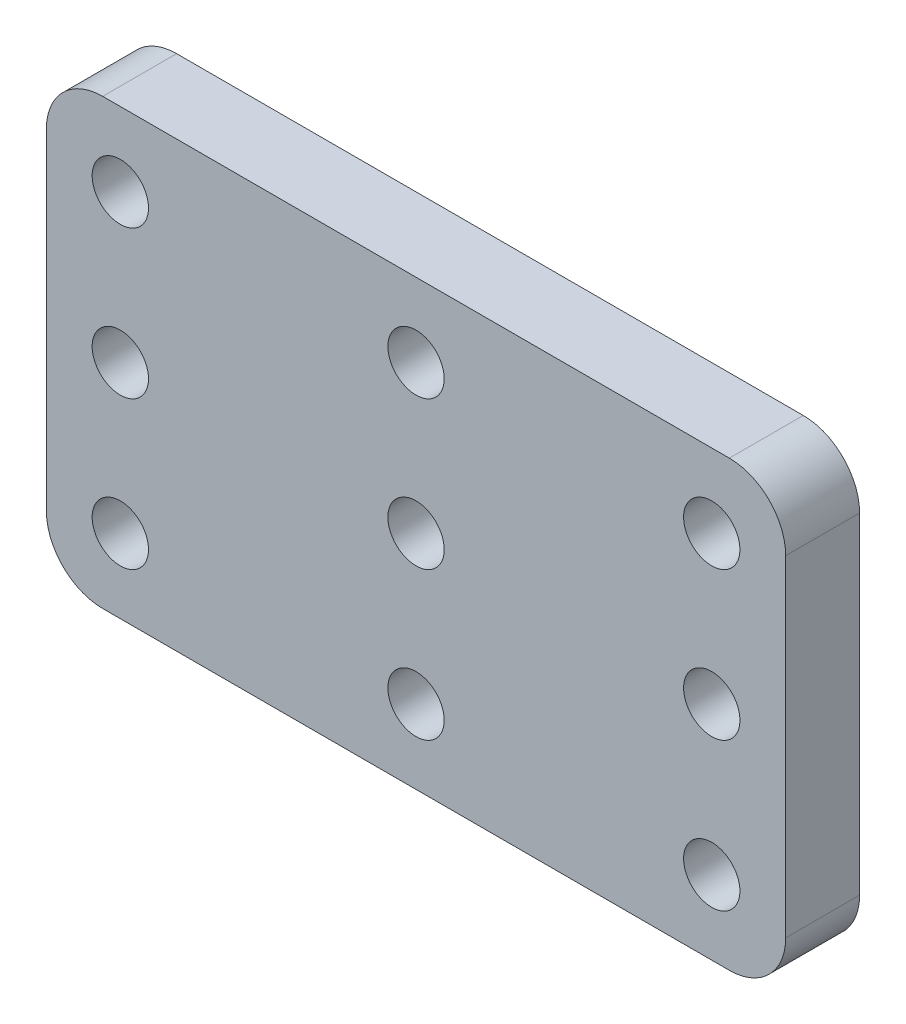
SolidWorks part; units mm, degrees
ref_plane "Front Plane" through (0, 0, 0) normal (0, 0, 1) x (1, 0, 0)
ref_plane "Top Plane" through (0, 0, 0) normal (0, 1, 0) x (1, 0, 0)
ref_plane "Right Plane" through (0, 0, 0) normal (1, 0, 0) x (0, 0, -1)
sketch "Sketch1" plane through (0, 0, 0) normal (0, 0, 1) x (1, 0, 0)
  line L1 (-24.9999, 15) -> (24.9999, 15)
  line L2 (-24.9999, 15) -> (-24.9999, -15)
  line L3 (-24.9999, -15) -> (25, -15)
  line L4 (24.9999, 15) -> (25, -15)
  line L5 (-24.9999, 15) -> (25, -15) construction
  line L6 (-24.9999, -15) -> (24.9999, 15) construction
  point P0 (0, 0)
  dimension "D1" = 29.9999
  dimension "D2" = 49.9999
extrude "Boss-Extrude1" add sketch "Sketch1" along normal blind 5
sketch "Sketch2" plane through (0, 0, 5) normal (0, 0, 1) x (1, 0, 0)
  line L0 (-24.9999, 15) -> (25, -15) construction
  line L1 (-24.9999, -15) -> (24.9999, 15) construction
  circle A0 centre (0, 0) radius 1.905
  dimension "D1" = 3.81
extrude "Cut-Extrude1" cut sketch "Sketch2" against normal up to surface (5 mm away) up to face at (0, 0, 0)
pattern_linear "LPattern1" count 2 spacing 10 along (0, 1, 0) count 2 spacing 10 along (0, -1, 0) of "Cut-Extrude1"
pattern_linear "LPattern2" count 2 spacing 20 along (-1, 0, 0) count 2 spacing 20 along (1, 0, 0) of "LPattern1", "Cut-Extrude1"
fillet "Fillet1" radius 3.81 4 edges at (24.9999, 15, 2.5) (25, -15, 2.5) (-24.9999, -15, 2.5) (-24.9999, 15, 2.5)
